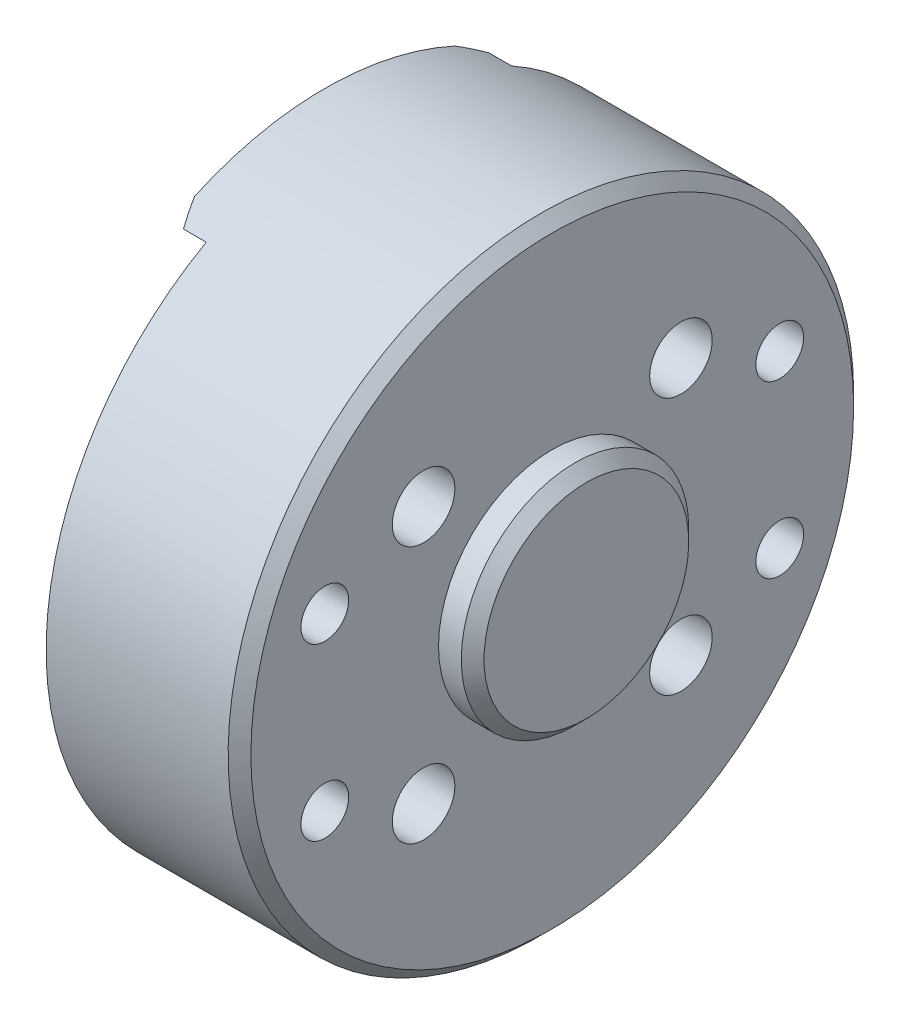
SolidWorks part; units mm, degrees
ref_plane "前视基准面" through (0, 0, 0) normal (0, 0, 1) x (1, 0, 0)
ref_plane "上视基准面" through (0, 0, 0) normal (0, 1, 0) x (1, 0, 0)
ref_plane "右视基准面" through (0, 0, 0) normal (1, 0, 0) x (0, 0, -1)
sketch "草图1" plane through (0, 0, 0) normal (1, 0, 0) x (0, 0, -1)
  circle A0 centre (0, 0) radius 27.5
  dimension "D1" = 55
extrude "凸台-拉伸1" add sketch "草图1" along normal mid plane 20
sketch "草图2" plane through (10, 0, 0) normal (1, 0, 0) x (0, 0, -1)
  circle A0 centre (0, 0) radius 10
  dimension "D1" = 20
extrude "凸台-拉伸2" add sketch "草图2" along normal blind 3
sketch "草图3" plane through (-10, 0, 0) normal (-1, 0, 0) x (0, 0, 1)
  line L0 (-42.0853, 0) -> (44.1341, 0) construction
  line L1 (0, 0) -> (0, 37.3048) construction
  line L2 (0, 0) -> (24.9889, 24.9889) construction
  circle A0 centre (11.3137, 11.3137) radius 2.75
  dimension "D1" = 16
  dimension "D2" = 5.5
  dimension "D3" = 45
extrude "切除-拉伸1" cut sketch "草图3" against normal blind 30
pattern_circular "阵列(圆周)1" count 4 every 90 about axis through (0, 0, 0) along (1, 0, 0) of "切除-拉伸1"
sketch "草图4" plane through (-10, 0, 0) normal (-1, 0, 0) x (0, 0, 1)
  circle A0 centre (-11.3137, 11.3137) radius 5
  dimension "D1" = 10
extrude "切除-拉伸2" cut sketch "草图4" against normal blind 10
pattern_circular "阵列(圆周)2" count 4 every 90 about axis through (0, 0, 0) along (1, 0, 0) of "切除-拉伸2"
sketch "草图5" plane through (-10, 0, 0) normal (-1, 0, 0) x (0, 0, 1)
  line L0 (-32.19, 0) -> (41.5565, 0) construction
  line L1 (41.5565, 0) -> (50.8045, -3.2605) construction
  line L2 (0, 30.7672) -> (0, -34.4427) construction
  line L4 (-28.9888, 24) -> (37.485, 24)
  line L5 (-28.9888, 24) -> (-28.9888, -24)
  line L6 (-28.9888, -24) -> (37.485, -24)
  line L7 (37.485, 24) -> (37.485, -24)
  dimension "D1" = 48
extrude "切除-拉伸3" cut sketch "草图5" against normal blind 3
chamfer "倒角1" distance 1 angle 45 2 edges at (-10, -24, 0) (-10, 24, 0)
chamfer "倒角2" distance 1 angle 45 2 edges at (13, 0, -10) (10, 0, -27.5)
hole_wizard "M5 螺纹孔1" positions "3D草图1" profile "草图6" tap size "M5" standard "Gb"
sketch3d "3D草图1"
  point P0 (-7, -7.5, -20)
  dimension "D1" = 7.5
  dimension "D2" = 20
sketch "草图6" plane through (-7, -7.5, -20) normal (0, 1, 0) x (0, 0, 1)
  line L0 (0, 0) -> (0, 33.6618)
  line L1 (0, 33.6618) -> (2.1, 32.4)
  line L2 (2.1, 32.4) -> (2.1, 0)
  line L5 (2.1, 0) -> (0, 0)
  line L10 (0, 33.6618) -> (-2.1, 32.4) construction
  line L11 (0, -6.35) -> (0, 107.95) construction
  dimension "螺纹孔钻头直径" = 4.2
  dimension "螺纹孔钻头深度" = 32.4
  dimension "导头角度" = 118
cosmetic thread "孔螺蚊线1" parameters "D1"=17, "D2"=5
mirror "镜向1" about plane through (0, 0, 0) normal (0, 1, 0) of "M5 螺纹孔1"
mirror "镜向2" about plane through (0, 0, 0) normal (0, 0, 1) of "镜向1", "M5 螺纹孔1"
